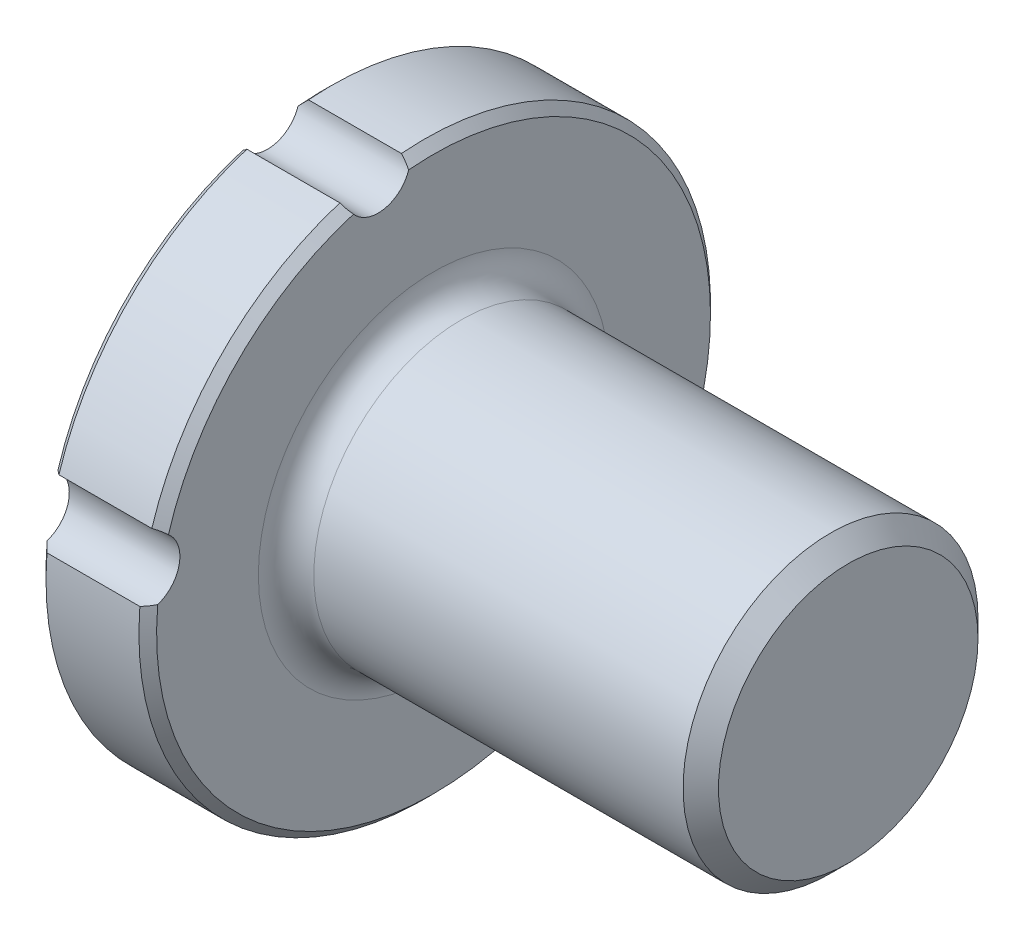
SolidWorks part; units mm, degrees
ref_plane "Front Plane" through (0, 0, 0) normal (1, 0, 0) x (0, 1, 0)
ref_plane "Top Plane" through (0, 0, 0) normal (0, 0, 1) x (0, 1, 0)
ref_plane "Right Plane" through (0, 0, 0) normal (0, 1, 0) x (-1, 0, 0)
sketch "Sketch1" plane through (0, 0, 0) normal (1, 0, 0) x (0, 1, 0)
  circle A0 centre (0, 0) radius 24.6126
extrude "Boss-Extrude1" add sketch "Sketch1" along normal blind 9.525
sketch "Sketch2" plane through (0, 0, 0) normal (1, 0, 0) x (0, 1, 0)
  circle A0 centre (0, 0) radius 12.7
extrude "Boss-Extrude2" add sketch "Sketch2" along normal blind 35.7124 from offset 9.525
sketch "Sketch3" plane through (0, 0, 0) normal (1, 0, 0) x (0, 1, 0)
  circle A0 centre (0, 0) radius 8.7122
extrude "Boss-Extrude4" add sketch "Sketch3" against normal blind 4.826
sketch "Sketch4" plane through (0, 0, 0) normal (1, 0, 0) x (0, 1, 0)
  circle A0 centre (24.6126, 44.45) radius 2.7686
  circle A1 centre (44.45, 24.6126) radius 2.7686
  circle A2 centre (24.6126, 4.7752) radius 2.7686
  circle A3 centre (4.7752, 24.6126) radius 2.7686
extrude "Cut-Extrude2" cut sketch "Sketch4" along normal through all
fillet "Fillet1" radius 0.381 1 edges at (0, 0, -8.7122)
fillet "Fillet2" radius 2.3876 1 edges at (9.525, 0, -12.7)
chamfer "Chamfer1" distance 0.762 angle 45 4 edges at (9.525, -17.4037, -17.4037) (9.525, 17.4037, 17.4037) (0, -17.4037, -17.4037) (0, 17.4037, 17.4037)
chamfer "Chamfer2" distance 1.524 angle 45 1 edges at (45.2374, 0, -12.7)
